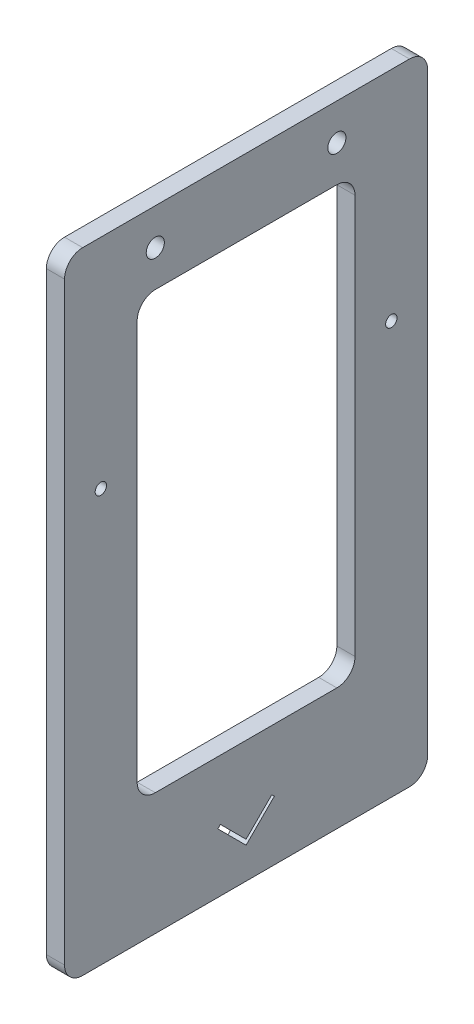
SolidWorks part; units mm, degrees
material "Balsa"
ref_plane "Front Plane" through (0, 0, 0) normal (0, 0, 1) x (1, 0, 0)
ref_plane "Top Plane" through (0, 0, 0) normal (0, 1, 0) x (1, 0, 0)
ref_plane "Right Plane" through (0, 0, 0) normal (1, 0, 0) x (0, 0, -1)
sketch "Sketch3" plane through (0, 0, 0) normal (1, 0, 0) x (0, 0, -1)
  line L0 (-31.75, -67.564) -> (31.75, -67.564)
  line L1 (-57.15, -110.236) -> (57.15, -110.236)
  line L2 (-63.5, -103.886) -> (-63.5, 103.886)
  line L3 (-57.15, 110.236) -> (57.15, 110.236)
  line L4 (63.5, -103.886) -> (63.5, 103.886)
  line L5 (-63.5, -110.236) -> (63.5, 110.236) construction
  line L6 (-63.5, 110.236) -> (63.5, -110.236) construction
  line L8 (-38.1, -61.214) -> (-38.1, 78.486)
  line L9 (-31.75, 84.836) -> (31.75, 84.836)
  line L11 (0, 0) -> (38.1, 84.836) construction
  line L12 (-38.1, 84.836) -> (0, 0) construction
  line L13 (38.1, -61.214) -> (38.1, 78.486)
  arc A0 (-57.15, -110.236) -> (-63.5, -103.886) centre (-57.15, -103.886) cw
  arc A1 (63.5, -103.886) -> (57.15, -110.236) centre (57.15, -103.886) cw
  arc A2 (63.5, 103.886) -> (57.15, 110.236) centre (57.15, 103.886) ccw
  arc A3 (-63.5, 103.886) -> (-57.15, 110.236) centre (-57.15, 103.886) cw
  arc A4 (31.75, -67.564) -> (38.1, -61.214) centre (31.75, -61.214) ccw
  arc A5 (-31.75, -67.564) -> (-38.1, -61.214) centre (-31.75, -61.214) cw
  arc A6 (31.75, 84.836) -> (38.1, 78.486) centre (31.75, 78.486) cw
  arc A7 (-38.1, 78.486) -> (-31.75, 84.836) centre (-31.75, 78.486) cw
  point P0 (0, 0)
  point P6 (0, 0)
  point P26 (38.1, -67.564)
  dimension "D7" = 6.35
  dimension "D8" = 6.35
  dimension "D1" = 220.472
  dimension "D2" = 127
  dimension "D3" = 76.2
  dimension "D4" = 152.4
  dimension "D5" = 25.4
  dimension "D6" = 25.4
extrude "Boss-Extrude2" add sketch "Sketch3" along normal blind 6.35
sketch "Sketch4" plane through (6.35, 0, 0) normal (1, 0, 0) x (0, 0, -1)
  line L0 (-57.15, -110.236) -> (57.15, -110.236) construction
  line L5 (0, -95.7399) -> (-8.9803, -86.7597) construction
  line L6 (-8.9803, -86.7597) -> (-9.8783, -87.6577) construction
  line L7 (0, -97.536) -> (-8.9803, -88.5557)
  line L8 (-9.8783, -87.6577) -> (0, -97.536) construction
  line L9 (0, -97.536) -> (9.8783, -87.6577) construction
  line L10 (9.8783, -87.6577) -> (8.9803, -86.7597) construction
  line L11 (8.9803, -86.7597) -> (0, -95.7399) construction
  line L12 (0, 3.4925) -> (0, -3.4925) construction
  line L13 (-8.9803, -88.5557) -> (-9.8783, -89.4538)
  line L14 (-9.8783, -89.4538) -> (0, -99.3321)
  line L15 (0, -97.536) -> (8.9803, -88.5557)
  line L16 (8.9803, -88.5557) -> (9.8783, -89.4538)
  line L17 (9.8783, -89.4538) -> (0, -99.3321)
  dimension "D1" = 12.7
  dimension "D2" = 12.7
  dimension "D3" = 1.27
  dimension "D4" = 12.7
  dimension "D5" = 1.27
extrude "Cut-Extrude1" cut sketch "Sketch4" against normal up to next
sketch "Sketch5" plane through (6.35, 0, 0) normal (1, 0, 0) x (0, 0, -1)
  line L0 (-31.75, 97.536) -> (31.75, 97.536) construction
  line L1 (31.75, 97.536) -> (63.5, 97.536) construction
  line L2 (63.5, -103.886) -> (63.5, 103.886) construction
  line L3 (-31.75, 97.536) -> (-63.5, 97.536) construction
  line L4 (-63.5, 103.886) -> (-63.5, -103.886) construction
  line L5 (57.15, 110.236) -> (-57.15, 110.236) construction
  circle A0 centre (-31.75, 97.536) radius 3.175
  circle A1 centre (31.75, 97.536) radius 3.175
  dimension "D1" = 6.35
  dimension "D2" = 63.5
  dimension "D3" = 12.7
extrude "Cut-Extrude2" cut sketch "Sketch5" against normal through all both and the other way through all
sketch "Sketch6" plane through (6.35, 0, 0) normal (1, 0, 0) x (0, 0, -1)
  line L0 (0, 3.4925) -> (0, -3.4925) construction
  line L1 (57.15, 110.236) -> (-57.15, 110.236) construction
  circle A0 centre (-50.8, 34.036) radius 1.9844
  circle A1 centre (50.8, 34.036) radius 1.9844
  point P4 (0, 0)
  dimension "D1" = 3.9688
  dimension "D2" = 50.8
  dimension "D3" = 76.2
extrude "Cut-Extrude3" cut sketch "Sketch6" against normal through all
